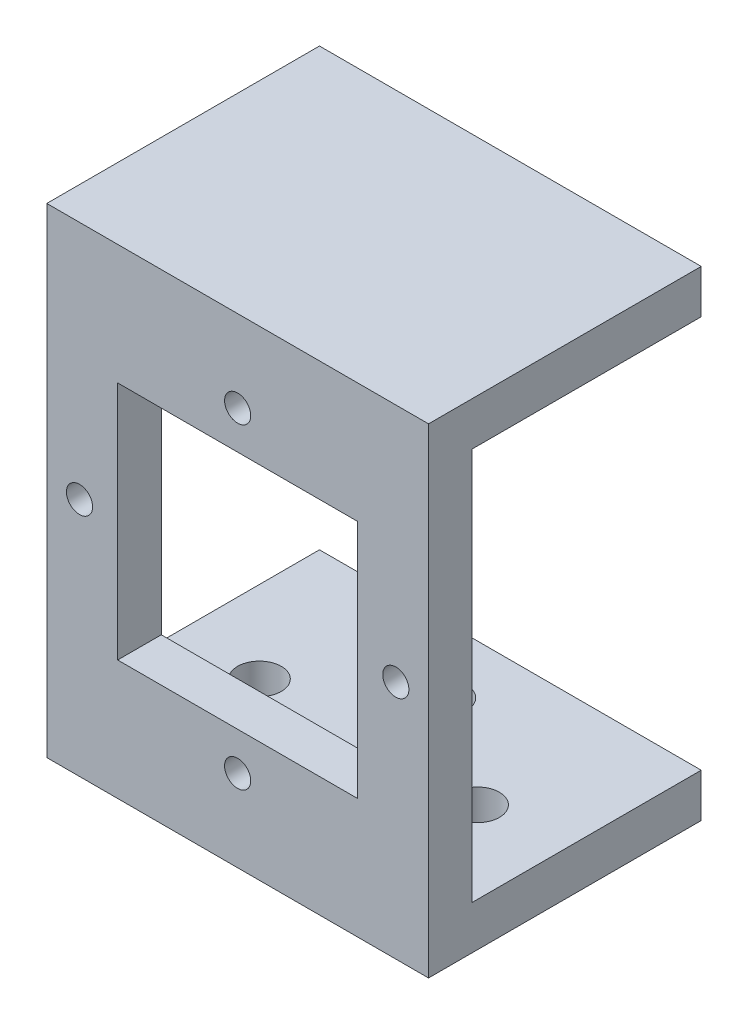
SolidWorks part; units mm, degrees
ref_plane "前视" through (0, 0, 0) normal (0, 0, 1) x (1, 0, 0)
ref_plane "上视" through (0, 0, 0) normal (0, 1, 0) x (1, 0, 0)
ref_plane "右视" through (0, 0, 0) normal (1, 0, 0) x (0, 0, -1)
sketch "草图1" plane through (0, 0, 0) normal (0, 0, 1) x (1, 0, 0)
  line L0 (0, 0) -> (0, 22) construction
  line L1 (11, -11) -> (-11, -11)
  line L2 (11, -11) -> (11, 11)
  line L3 (11, 11) -> (-11, 11)
  line L4 (-11, -11) -> (-11, 11)
  line L5 (11, -11) -> (-11, 11) construction
  line L6 (11, 11) -> (-11, -11) construction
  line L7 (-17.5, 0) -> (17.5, 0) construction
  line L8 (17.5, 0) -> (17.5, -18)
  line L9 (17.5, -18) -> (-17.5, -18)
  line L10 (-17.5, 0) -> (-17.5, -18)
  line L11 (-17.5, 0) -> (-17.5, 18)
  line L12 (-17.5, 18) -> (17.5, 18)
  line L13 (17.5, 18) -> (17.5, 0)
  circle A1 centre (0, 14.5) radius 1.2
  circle A2 centre (14.5, 0) radius 1.2
  circle A3 centre (0, -14.5) radius 1.2
  circle A4 centre (-14.5, 0) radius 1.2
  point P0 (0, 0)
  point P14 (0, 0)
  point P17 (0, 0)
  point P20 (0, 0)
  point P23 (0, 0)
  dimension "D3" = 35
  dimension "D7" = 2.4
  dimension "D1" = 22
  dimension "D2" = 22
  dimension "D4" = 14.5
  dimension "D6" = 18
  dimension "D8" = 18
  dimension "D5" = 4
extrude "凸台-拉伸1" add sketch "草图1" along normal blind 4
sketch "草图2" plane through (0, -18, 0) normal (0, -1, 0) x (1, 0, 0)
  line L0 (0, 0) -> (0, -21) construction
  line L1 (17.5, 4) -> (-17.5, 4)
  line L2 (17.5, 4) -> (17.5, -21)
  line L3 (17.5, -21) -> (-17.5, -21)
  line L4 (-17.5, 4) -> (-17.5, -21)
  line L5 (-17.5, 0) -> (17.5, 0) construction
  circle A0 centre (10, -8) radius 2
  circle A1 centre (0, -15) radius 2
  circle A2 centre (-10, -8) radius 2
  dimension "D4" = 4
  dimension "D5" = 4
  dimension "D6" = 10
  dimension "D1" = 25
  dimension "D2" = 8
  dimension "D3" = 6
extrude "凸台-拉伸2" add sketch "草图2" along normal blind 4
sketch "草图3" plane through (0, 18, 0) normal (0, 1, 0) x (1, 0, 0)
  line L1 (-17.5, -4) -> (17.5, -4)
  line L2 (-17.5, -4) -> (-17.5, 21)
  line L3 (-17.5, 21) -> (17.5, 21)
  line L4 (17.5, -4) -> (17.5, 21)
  dimension "D1" = 35
  dimension "D2" = 25
extrude "凸台-拉伸3" add sketch "草图3" along normal blind 4
sketch "草图4" plane through (0, -22, 0) normal (0, -1, 0) x (1, 0, 0)
  line L0 (0, 4) -> (0, -21)
  line L1 (17.5, 4) -> (-17.5, 4) construction
  line L2 (-17.5, -21) -> (17.5, -21) construction
